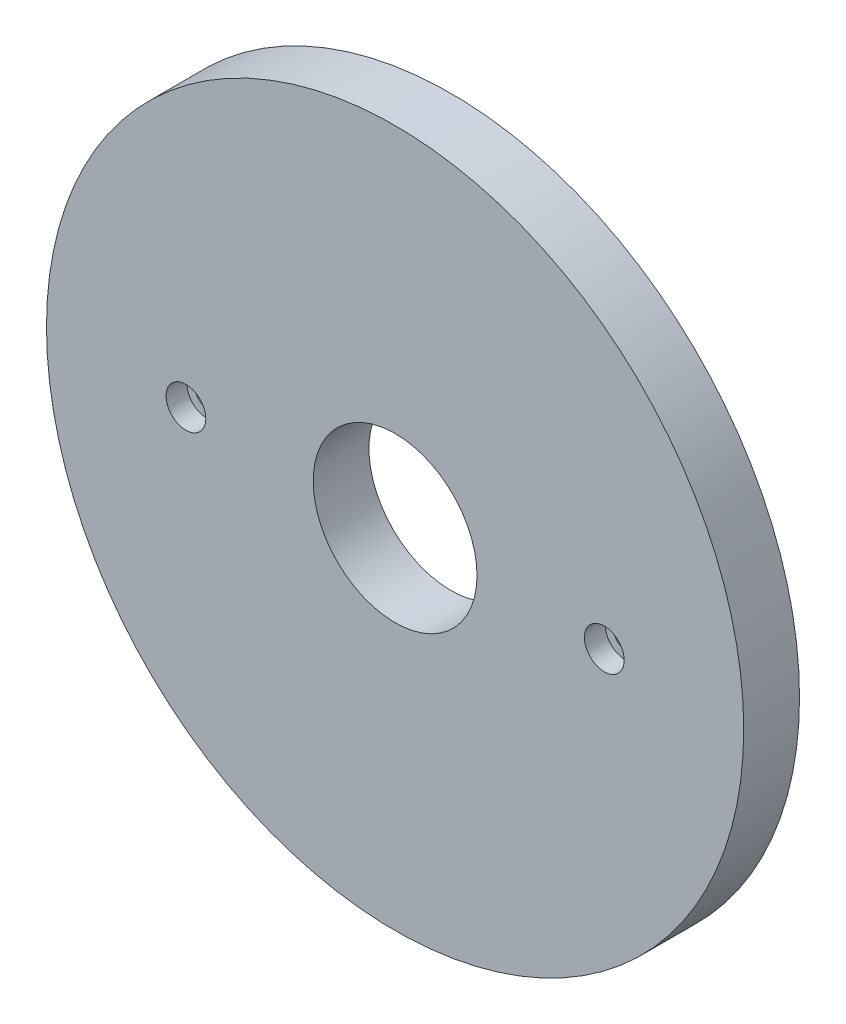
SolidWorks part; units mm, degrees
ref_plane "Plan de face" through (0, 0, 0) normal (0, 0, 1) x (1, 0, 0)
ref_plane "Plan de dessus" through (0, 0, 0) normal (0, 1, 0) x (1, 0, 0)
ref_plane "Plan de droite" through (0, 0, 0) normal (1, 0, 0) x (0, 0, -1)
sketch "Esquisse1" plane through (0, 0, 0) normal (0, 0, 1) x (1, 0, 0)
  circle A0 centre (0, 0) radius 50
  circle A1 centre (0, 0) radius 11.75
  dimension "D1" = 100
  dimension "D2" = 23.5
extrude "Boss.-Extru.1" add sketch "Esquisse1" against normal blind 8
sketch "Esquisse2" plane through (0, 0, 0) normal (0, 0, 1) x (1, 0, 0)
  circle A0 centre (30, 0) radius 1.6
  circle A1 centre (-30, 0) radius 1.6
  dimension "D1" = 30
  dimension "D2" = 3.2
  dimension "D3" = 3.2
  dimension "D4" = 30
extrude "Enlèv. mat.-Extru.1" cut sketch "Esquisse2" against normal through all
sketch "Esquisse3" plane through (0, 0, 0) normal (0, 0, 1) x (1, 0, 0)
  circle A0 centre (30, 0) radius 2.85
  circle A1 centre (-30, 0) radius 2.85
  dimension "D1" = 5.7
  dimension "D2" = 5.7
extrude "Enlèv. mat.-Extru.2" cut sketch "Esquisse3" against normal blind 3
